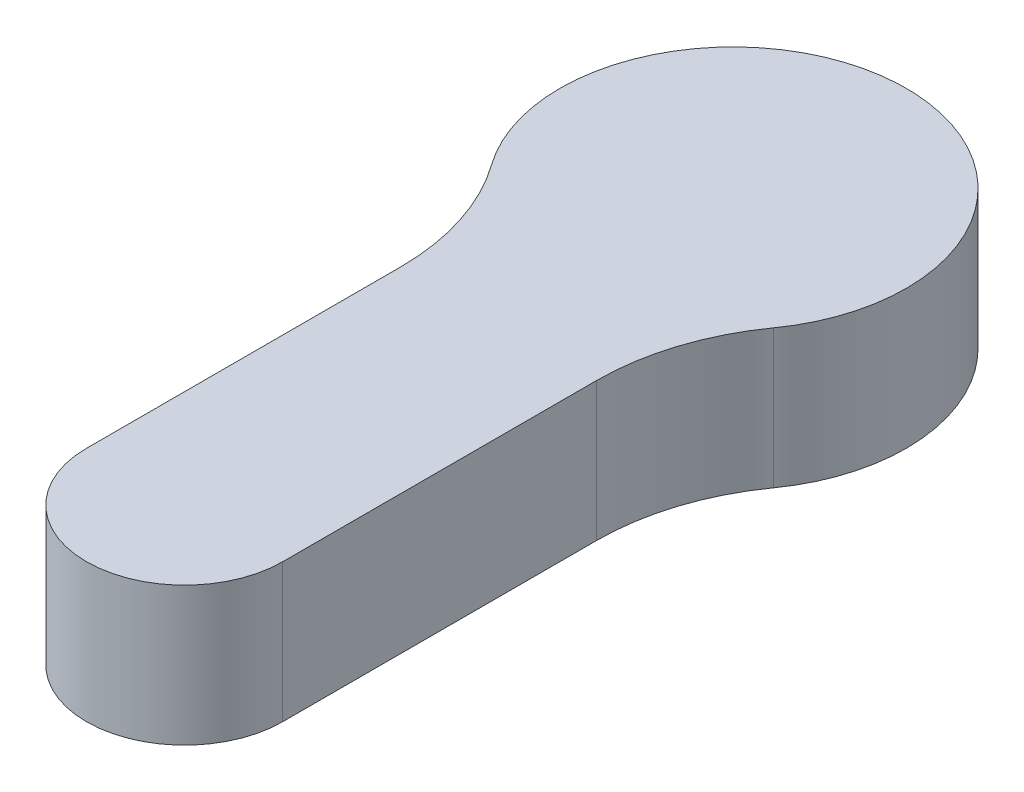
SolidWorks part; units mm, degrees
ref_plane "Front Plane" through (0, 0, 0) normal (0, 0, 1) x (1, 0, 0)
ref_plane "Top Plane" through (0, 0, 0) normal (0, 1, 0) x (1, 0, 0)
ref_plane "Right Plane" through (0, 0, 0) normal (1, 0, 0) x (0, 0, -1)
sketch "Sketch1" plane through (0, 0, 0) normal (0, 1, 0) x (1, 0, 0)
  line L0 (0, 0) -> (0, -23.75)
  line L1 (-4.25, 0) -> (-4.25, -23.75)
  line L2 (4.25, 0) -> (4.25, -23.75)
  circle A0 centre (0, 0) radius 7.5
  arc A1 (-4.25, 0) -> (4.25, 0) centre (0, 0) cw
  arc A2 (-4.25, -23.75) -> (4.25, -23.75) centre (0, -23.75) ccw
  point P8 (0, -28)
  dimension "D1" = 15
  dimension "D4" = 28
  dimension "D2" = 4.25
  dimension "D3" = 4.25
extrude "Boss-Extrude1" add sketch "Sketch1" along normal blind 6
fillet "Fillet1" radius 10 2 edges at (-4.25, 3, 6.1796) (4.25, 3, 6.1796)
